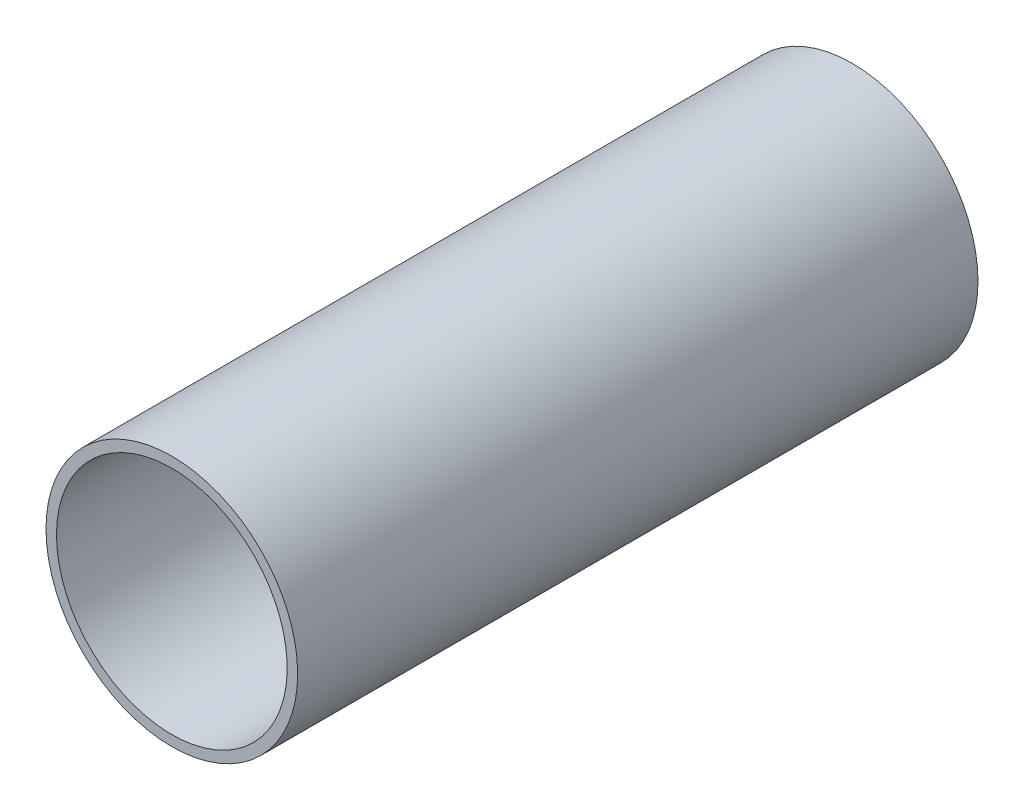
SolidWorks part; units mm, degrees
ref_plane "Front Plane" through (0, 0, 0) normal (0, 0, 1) x (1, 0, 0)
ref_plane "Top Plane" through (0, 0, 0) normal (0, 1, 0) x (1, 0, 0)
ref_plane "Right Plane" through (0, 0, 0) normal (1, 0, 0) x (0, 0, -1)
sketch "Sketch1" plane through (0, 0, 0) normal (0, 0, 1) x (1, 0, 0)
  circle A0 centre (0, 0) radius 69.85
  point P3 (-57.5907, 2.1462)
extrude "Boss-Extrude4" add sketch "Sketch1" along normal blind 412
sketch "Sketch3" plane through (0, 0, 412) normal (0, 0, 1) x (1, 0, 0)
  circle A0 centre (0, 0) radius 76.2
extrude "Boss-Extrude5" add sketch "Sketch3" against normal blind 412
sketch "Sketch4" plane through (0, 0, 0) normal (0, 0, -1) x (-1, 0, 0)
  circle A0 centre (0, 0) radius 69.85
extrude "Cut-Extrude2" cut sketch "Sketch4" against normal blind 412
